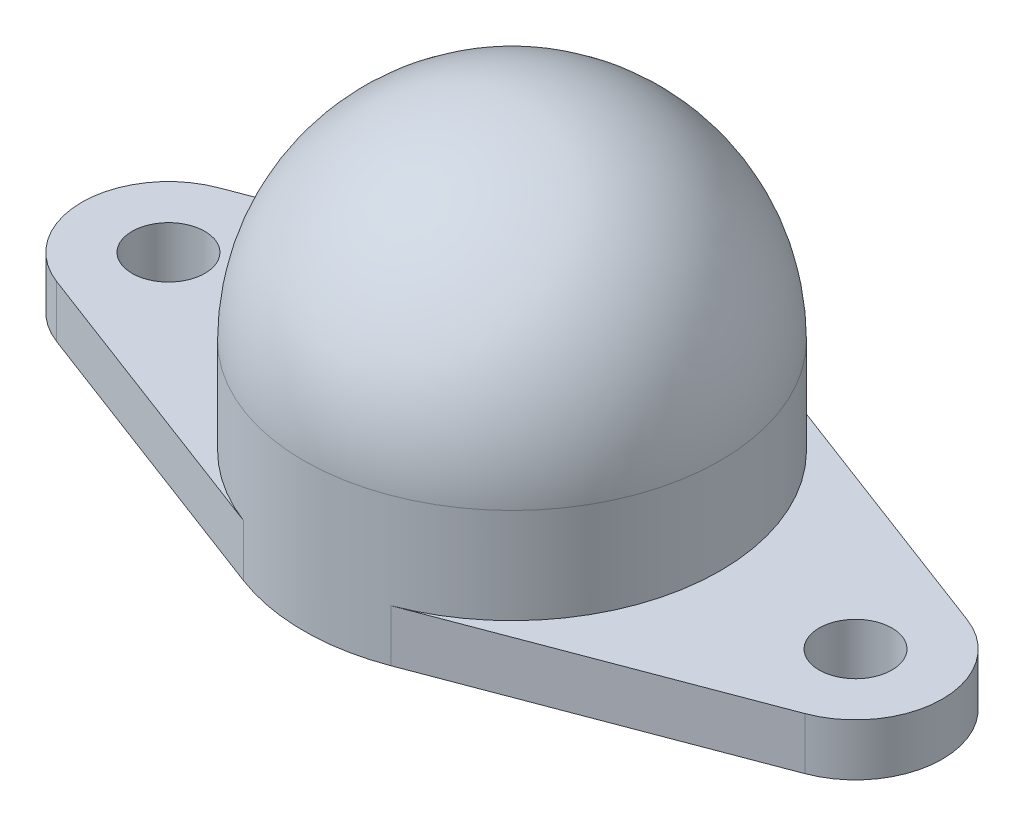
SolidWorks part; units mm, degrees
ref_plane "Front Plane" through (0, 0, 0) normal (0, 0, 1) x (1, 0, 0)
ref_plane "Top Plane" through (0, 0, 0) normal (0, 1, 0) x (1, 0, 0)
ref_plane "Right Plane" through (0, 0, 0) normal (1, 0, 0) x (0, 0, -1)
sketch "Sketch1" plane through (0, 0, 0) normal (0, 1, 0) x (1, 0, 0)
  line L2 (-21.5677, 4.6771) -> (-4.2424, 11.2251)
  line L3 (21.5677, -4.6771) -> (4.2424, -11.2251)
  line L4 (-21.5677, -4.6771) -> (-4.2424, -11.2251)
  line L5 (21.5677, 4.6771) -> (4.2424, 11.2251)
  circle A0 centre (-19.8, 0) radius 2.1
  arc A2 (-21.5677, 4.6771) -> (-21.5677, -4.6771) centre (-19.8, 0) ccw
  arc A3 (-4.2424, -11.2251) -> (4.2424, -11.2251) centre (0, 0) ccw
  arc A4 (4.2424, 11.2251) -> (-4.2424, 11.2251) centre (0, 0) ccw
  arc A5 (21.5677, 4.6771) -> (21.5677, -4.6771) centre (19.8, 0) cw
  circle A6 centre (19.8, 0) radius 2.1
extrude "Boss-Extrude1" add sketch "Sketch1" along normal blind 3
sketch "Sketch2" plane through (0, 3, 0) normal (0, 1, 0) x (1, 0, 0)
  circle A0 centre (0, 0) radius 12
extrude "Boss-Extrude3" add sketch "Sketch2" along normal blind 17.5
fillet "Fillet1" radius 12 1 edges at (0, 20.5, 12)
